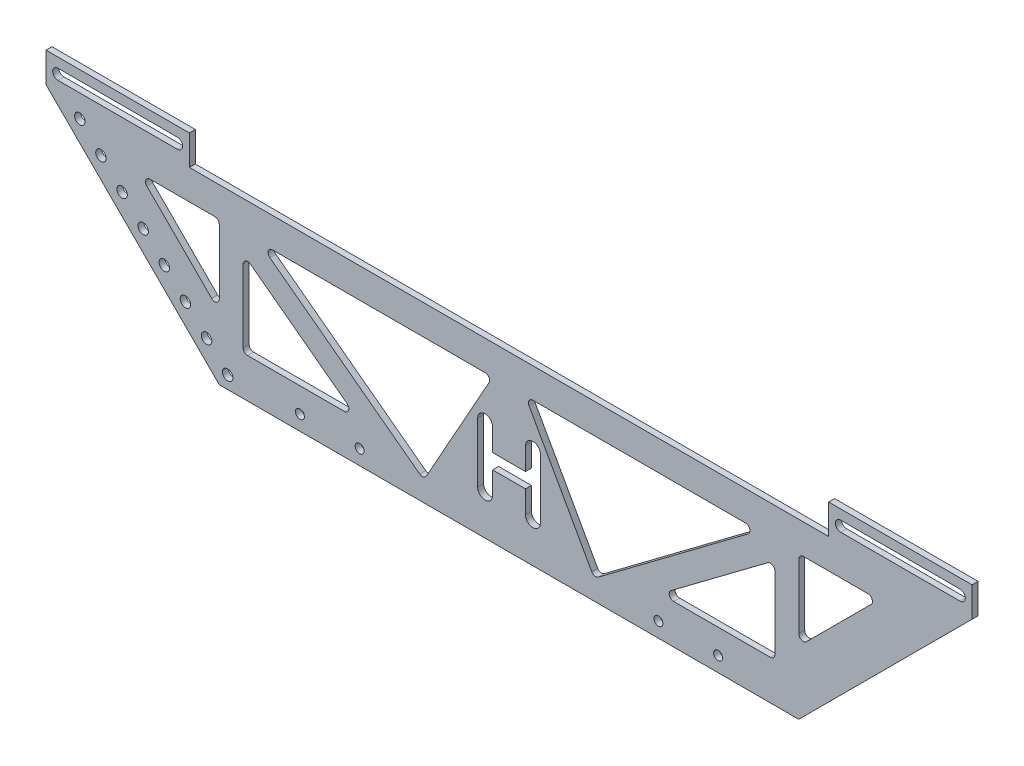
SolidWorks part; units mm, degrees
material "A-玻璃纤维"
ref_plane "前视基准面" through (0, 0, 0) normal (0, 0, 1) x (1, 0, 0)
ref_plane "上视基准面" through (0, 0, 0) normal (0, 1, 0) x (1, 0, 0)
ref_plane "右视基准面" through (0, 0, 0) normal (1, 0, 0) x (0, 0, -1)
sketch "草图1" plane through (0, 0, 0) normal (0, 0, 1) x (1, 0, 0)
  line L0 (-107, 30) -> (-107, 0)
  line L1 (-107, 0) -> (107, 0)
  line L2 (107, 0) -> (107, 30)
  line L3 (-107, 30) -> (-155, 30)
  line L5 (-97, -58) -> (97, -58)
  line L7 (155, 30) -> (107, 30)
  line L8 (0, 0) -> (0, -58) construction
  line L9 (-151, 25) -> (-111, 25) construction
  line L10 (-151, 25) -> (-151, 5) construction
  line L11 (-151, 5) -> (-111, 5) construction
  line L12 (-111, 25) -> (-111, 5) construction
  line L13 (111, 25) -> (111, 5) construction
  line L14 (151, 5) -> (111, 5) construction
  line L15 (151, 25) -> (151, 5) construction
  line L16 (151, 25) -> (111, 25) construction
  line L17 (-70, -53) -> (-50, -53) construction
  line L18 (70, -53) -> (50, -53) construction
  line L19 (-155, 30) -> (-155, 0)
  line L20 (-155, 0) -> (-97, -58)
  line L21 (97, -58) -> (155, 0)
  line L22 (155, 0) -> (155, 30)
  circle A0 centre (-151, 25) radius 1.5
  circle A1 centre (-111, 25) radius 1.5
  circle A2 centre (-111, 5) radius 1.5
  circle A3 centre (-151, 5) radius 1.5
  circle A4 centre (151, 5) radius 1.5
  circle A5 centre (111, 5) radius 1.5
  circle A6 centre (111, 25) radius 1.5
  circle A7 centre (151, 25) radius 1.5
  circle A8 centre (-70, -53) radius 1.5
  circle A9 centre (-50, -53) radius 1.5
  circle A10 centre (50, -53) radius 1.5
  circle A11 centre (70, -53) radius 1.5
  point P4 (0, 0)
  dimension "D5" = 3
  dimension "D10" = 3
  dimension "D1" = 30
  dimension "D2" = 214
  dimension "D3" = 58
  dimension "D4" = 48
  dimension "D6" = 5
  dimension "D7" = 5
  dimension "D8" = 4
  dimension "D9" = 4
  dimension "D11" = 20
  dimension "D12" = 50
  dimension "D13" = 5
  dimension "D14" = 45
extrude "凸台-拉伸1" add sketch "草图1" along normal blind 2
sketch "草图3" plane through (0, 0, 2) normal (0, 0, 1) x (1, 0, 0)
  line L0 (155, 0) -> (155, 30) construction
  line L1 (-155, 30) -> (155, 30)
  line L2 (-155, 30) -> (-155, 10)
  line L3 (-155, 10) -> (155, 10)
  line L4 (155, 30) -> (155, 10)
  circle A0 centre (151, 5) radius 1.5 construction
  dimension "D1" = 5
extrude "切除-拉伸2" cut sketch "草图3" against normal through all
sketch "草图4" plane through (0, 0, 2) normal (0, 0, 1) x (1, 0, 0)
  line L0 (-121.2261, -12.5607) -> (-99.5607, -34.2261)
  line L1 (-97, -33.1655) -> (-97, -11.5)
  line L2 (-98.5, -10) -> (-120.1655, -10)
  line L3 (107, 0) -> (-107, 0) construction
  line L4 (-155, 0) -> (-97, -58) construction
  line L5 (0, 0) -> (0, -58) construction
  line L6 (-97, -58) -> (97, -58) construction
  line L10 (-89, -19) -> (-89, -43.2868)
  line L11 (-87.5, -44.7868) -> (-55.1176, -44.7868)
  line L12 (-54.2176, -42.0868) -> (-86.6, -17.8)
  line L13 (-79.1667, -10) -> (-8, -10)
  line L14 (-6.6902, -12.231) -> (-27.6902, -49.856)
  line L15 (-29.9, -50.325) -> (-80.0667, -12.7)
  line L20 (29.9, -50.325) -> (80.0667, -12.7)
  line L21 (6.6902, -12.231) -> (27.6902, -49.856)
  line L22 (79.1667, -10) -> (8, -10)
  line L23 (54.2176, -42.0868) -> (86.6, -17.8)
  line L24 (87.5, -44.7868) -> (55.1176, -44.7868)
  line L25 (89, -19) -> (89, -43.2868)
  line L26 (98.5, -10) -> (120.1655, -10)
  line L27 (97, -33.1655) -> (97, -11.5)
  line L28 (121.2261, -12.5607) -> (99.5607, -34.2261)
  line L32 (0, 0) -> (0, -58)
  line L33 (0, -10.8561) -> (0, -58)
  line L37 (-5.5, -36.928) -> (-5.5, -44.428)
  line L41 (-5.5, -31.928) -> (5.5, -31.928)
  line L42 (-5.5, -36.928) -> (5.5, -36.928)
  line L44 (-5.5, -24.428) -> (-5.5, -31.928)
  line L45 (-10.5, -24.428) -> (-10.5, -44.428)
  line L47 (10.5, -24.428) -> (10.5, -44.428)
  line L48 (5.5, -24.428) -> (5.5, -31.928)
  line L49 (5.5, -36.928) -> (5.5, -44.428)
  arc A4 (-8, -10) -> (-6.6902, -12.231) centre (-8, -11.5) cw
  arc A5 (-27.6902, -49.856) -> (-29.9, -50.325) centre (-29, -49.125) cw
  arc A6 (-79.1667, -10) -> (-80.0667, -12.7) centre (-79.1667, -11.5) ccw
  arc A7 (-55.1176, -44.7868) -> (-54.2176, -42.0868) centre (-55.1176, -43.2868) ccw
  arc A8 (-89, -43.2868) -> (-87.5, -44.7868) centre (-87.5, -43.2868) ccw
  arc A9 (-89, -19) -> (-86.6, -17.8) centre (-87.5, -19) cw
  arc A10 (-99.5607, -34.2261) -> (-97, -33.1655) centre (-98.5, -33.1655) ccw
  arc A11 (-97, -11.5) -> (-98.5, -10) centre (-98.5, -11.5) ccw
  arc A12 (-121.2261, -12.5607) -> (-120.1655, -10) centre (-120.1655, -11.5) cw
  arc A13 (121.2261, -12.5607) -> (120.1655, -10) centre (120.1655, -11.5) ccw
  arc A14 (97, -11.5) -> (98.5, -10) centre (98.5, -11.5) cw
  arc A15 (99.5607, -34.2261) -> (97, -33.1655) centre (98.5, -33.1655) cw
  arc A16 (89, -19) -> (86.6, -17.8) centre (87.5, -19) ccw
  arc A17 (89, -43.2868) -> (87.5, -44.7868) centre (87.5, -43.2868) cw
  arc A18 (55.1176, -44.7868) -> (54.2176, -42.0868) centre (55.1176, -43.2868) cw
  arc A19 (79.1667, -10) -> (80.0667, -12.7) centre (79.1667, -11.5) cw
  arc A20 (27.6902, -49.856) -> (29.9, -50.325) centre (29, -49.125) ccw
  arc A21 (8, -10) -> (6.6902, -12.231) centre (8, -11.5) ccw
  arc A27 (-5.5, -24.428) -> (-10.5, -24.428) centre (-8, -24.428) ccw
  arc A28 (-10.5, -44.428) -> (-5.5, -44.428) centre (-8, -44.428) ccw
  arc A29 (10.5, -24.428) -> (5.5, -24.428) centre (8, -24.428) ccw
  arc A30 (5.5, -44.428) -> (10.5, -44.428) centre (8, -44.428) ccw
  point P26 (0, -34.428)
  point P32 (-8, -34.428)
  point P37 (8, -34.428)
  point P46 (-83.6667, -10)
  point P51 (-89, -44.7868)
  point P54 (-89, -16)
  point P59 (-97, -10)
  point P89 (97, -10)
  point P90 (89, -16)
  point P91 (89, -44.7868)
  point P92 (83.6667, -10)
  dimension "D7" = 1.5
  dimension "D1" = 10
  dimension "D2" = 15
  dimension "D3" = 8
  dimension "D4" = 8
  dimension "D5" = 6
  dimension "D6" = 8
  dimension "D8" = 29
extrude "切除-拉伸3" cut sketch "草图4" against normal through all and the other way through all contours L49 A30 L47 A29 L48 L41 L33 L42 | L45 A28 L37 L42 L33 L41 L44 A27 | L13 A6 L15 A5 L14 A4 | A9 L10 A8 L11 A7 L12 | A12 L0 A10 L1 A11 L2 | L22 A21 L21 A20 L20 A19 | A18 L24 A17 L25 A16 L23 | A15 L28 A13 L26 A14 L27
sketch "草图5" plane through (0, 0, 2) normal (0, 0, 1) x (1, 0, 0)
  line L0 (-151, 5) -> (-111, 5) construction
  line L1 (-151, 6.75) -> (-111, 6.75)
  line L2 (-151, 3.25) -> (-111, 3.25)
  line L3 (111, 5) -> (151, 5) construction
  line L4 (111, 6.75) -> (151, 6.75)
  line L5 (111, 3.25) -> (151, 3.25)
  arc A0 (-151, 6.75) -> (-151, 3.25) centre (-151, 5) ccw
  arc A1 (-111, 3.25) -> (-111, 6.75) centre (-111, 5) ccw
  arc A2 (111, 6.75) -> (111, 3.25) centre (111, 5) ccw
  arc A3 (151, 3.25) -> (151, 6.75) centre (151, 5) ccw
  point P4 (-131, 5)
  point P13 (131, 5)
extrude "切除-拉伸4" cut sketch "草图5" against normal through all
sketch "草图7" plane through (0, 0, 2) normal (0, 0, 1) x (1, 0, 0)
  line L0 (-155, 0) -> (-151.4645, 3.5355)
  line L1 (-151.4645, 3.5355) -> (-86.2465, -61.6824)
  line L2 (-126, -29) -> (-122.4645, -25.4645)
  line L3 (-155, 0) -> (-97, -58) construction
  line L4 (-122.4645, -25.4645) -> (-129.5355, -18.3934)
  line L5 (-129.5355, -18.3934) -> (-134.2335, -13.6955)
  line L6 (-129.5355, -18.3934) -> (-136.6066, -11.3223)
  line L7 (-136.6066, -11.3223) -> (-143.6777, -4.2513)
  line L8 (-122.4645, -25.4645) -> (-115.3934, -32.5355)
  line L9 (-115.3934, -32.5355) -> (-108.3223, -39.6066)
  line L10 (-108.3223, -39.6066) -> (-101.2513, -46.6777)
  line L11 (-101.2513, -46.6777) -> (-94.1802, -53.7487)
  line L12 (0, 0) -> (0, -58)
  line L13 (-97, -58) -> (97, -58) construction
  circle A0 centre (-122.4645, -25.4645) radius 1.75
  circle A1 centre (-129.5355, -18.3934) radius 1.75
  circle A2 centre (-136.6066, -11.3223) radius 1.75
  circle A3 centre (-143.6777, -4.2513) radius 1.75
  circle A4 centre (-115.3934, -32.5355) radius 1.75
  circle A5 centre (-108.3223, -39.6066) radius 1.75
  circle A6 centre (-101.2513, -46.6777) radius 1.75
  circle A7 centre (-94.1802, -53.7487) radius 1.75
  circle A8 centre (94.1802, -53.7487) radius 1.75
  circle A9 centre (101.2513, -46.6777) radius 1.75
  circle A10 centre (108.3223, -39.6066) radius 1.75
  circle A11 centre (115.3934, -32.5355) radius 1.75
  circle A12 centre (122.4645, -25.4645) radius 1.75
  circle A13 centre (129.5355, -18.3934) radius 1.75
  circle A14 centre (136.6066, -11.3223) radius 1.75
  circle A15 centre (143.6777, -4.2513) radius 1.75
  dimension "D1" = 3.5
  dimension "D2" = 10
  dimension "D3" = 10
  dimension "D4" = 10
  dimension "D5" = 10
  dimension "D6" = 10
  dimension "D7" = 10
  dimension "D8" = 10
extrude "切除-拉伸6" cut sketch "草图7" against normal through all contours L1 A7 | L1 A7 | L1 A6 | L1 A6 | L1 A5 | L1 A5 | L1 A4 | L1 A4 | L1 A0 L4 | L2 A0 L1 | L4 A0 L2 | L1 A1 L6 | L6 A1 L1 | L1 A2 L7 | L7 A2 L1 | L1 A3 | L1 A3
